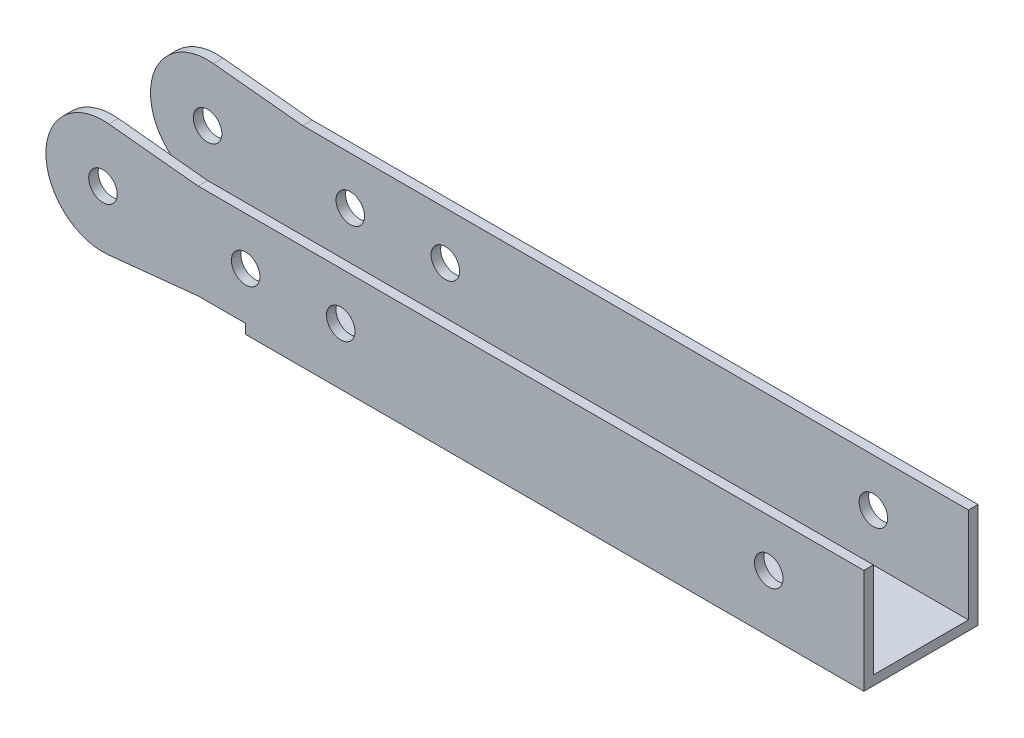
SolidWorks part; units mm, degrees
ref_plane "前视基准面" through (0, 0, 0) normal (0, 0, 1) x (1, 0, 0)
ref_plane "上视基准面" through (0, 0, 0) normal (0, 1, 0) x (1, 0, 0)
ref_plane "右视基准面" through (0, 0, 0) normal (1, 0, 0) x (0, 0, -1)
sketch "草图1" plane through (0, 0, 0) normal (0, 0, 1) x (1, 0, 0)
  line L0 (43.2, 8.0104) -> (-26.8, 8.0104)
  line L1 (-26.8, -2) -> (43.2, -2)
  line L2 (-60.7008, 3) -> (100.6682, 3) construction
  line L3 (43.2, 8.0104) -> (43.2, -2)
  line L6 (-26.8, 8.0104) -> (-36.1907, 8.969)
  line L7 (-26.8, -2) -> (-36.1842, -2.9683)
  circle A0 centre (-36.8, 3) radius 1.5
  arc A1 (-36.1907, 8.969) -> (-36.1842, -2.9683) centre (-36.8, 3) ccw
  circle A2 centre (-21.8, 3) radius 1.5
  circle A3 centre (-11.8, 3) radius 1.5
  circle A4 centre (33.2, 3) radius 1.5
  dimension "D1" = 5
  dimension "D4" = 15
  dimension "D5" = 3
  dimension "D6" = 12
  dimension "D2" = 3
  dimension "D3" = 25
  dimension "D7" = 3
  dimension "D8" = 10
  dimension "D9" = 10
  dimension "D10" = 70
  dimension "D12" = 70
ref_plane "基准面1" through (0, -2, 0) normal (0, -1, 0) x (1, 0, 0)
ref_plane "基准面2" through (0, 0, 10) normal (0, 0, 1) x (1, 0, 0)
sketch "草图3" plane through (0, 0, 10) normal (0, 0, 1) x (1, 0, 0)
  line L5 (-26.8, 8.0104) -> (-36.1907, 8.969)
  line L6 (43.2, 8.0104) -> (-26.8, 8.0104)
  line L7 (43.2, -2) -> (43.2, 8.0104)
  line L8 (-26.8, -2) -> (43.2, -2)
  line L9 (-36.1842, -2.9683) -> (-26.8, -2)
  line L10 (-26.8, 8.0104) -> (-36.1907, 8.969)
  line L11 (43.2, 8.0104) -> (-26.8, 8.0104)
  line L12 (43.2, -2) -> (43.2, 8.0104)
  line L13 (-26.8, -2) -> (43.2, -2)
  line L14 (-36.1842, -2.9683) -> (-26.8, -2)
  circle A1 centre (33.2, 3) radius 1.5
  circle A2 centre (33.2, 3) radius 1.5
  circle A3 centre (-11.8, 3) radius 1.5
  circle A4 centre (-11.8, 3) radius 1.5
  circle A5 centre (-21.8, 3) radius 1.5
  circle A6 centre (-21.8, 3) radius 1.5
  circle A7 centre (-36.8, 3) radius 1.5
  circle A8 centre (-36.8, 3) radius 1.5
  arc A9 (-36.1907, 8.969) -> (-36.1842, -2.9683) centre (-36.8, 3) ccw
  arc A10 (-36.1907, 8.969) -> (-36.1842, -2.9683) centre (-36.8, 3) ccw
  dimension "D1" = 0
  dimension "D2" = 0
  dimension "D3" = 0
  dimension "D4" = 0
  dimension "D5" = 0
extrude "凸台-拉伸1" add sketch "草图3" along normal blind 1
extrude "凸台-拉伸2" add sketch "草图1" against normal blind 1 separate body
sketch "草图4" plane through (0, -2, 0) normal (0, -1, 0) x (1, 0, 0)
  line L0 (43.2, 11) -> (43.2, -1)
  line L1 (43.2, -1) -> (-21.8, -1)
  line L2 (-26.8, -1) -> (43.2, -1) construction
  line L3 (-21.8, -1) -> (-21.8, 11)
  line L4 (-26.8, 11) -> (43.2, 11) construction
  line L5 (-21.8, 11) -> (43.2, 11)
  line L6 (-36.8, 6.7279) -> (-36.8, -2.3916) construction
  line L7 (-36.8, 11) -> (-36.8, 10) construction
  dimension "D1" = 15
extrude "凸台-拉伸3" add sketch "草图4" along normal blind 1
